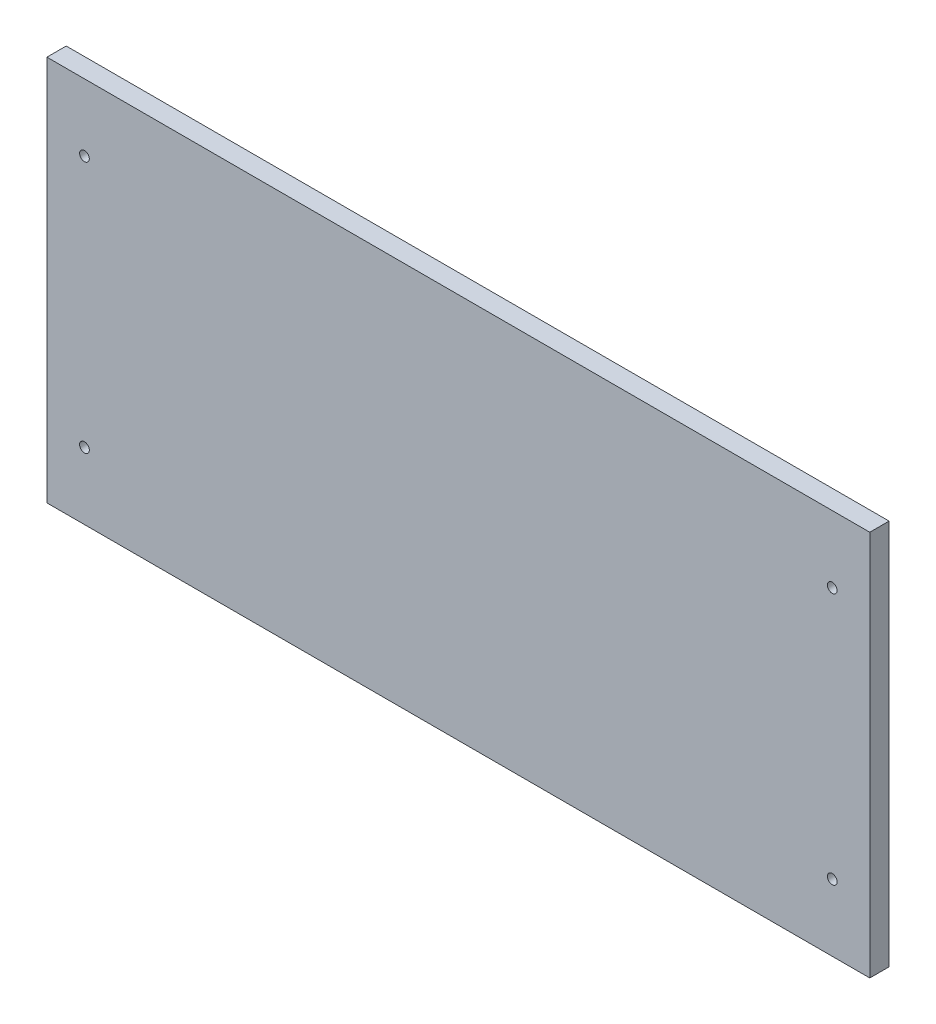
SolidWorks part; units mm, degrees
material "Acrylic (Medium-high impact)"
ref_plane "Front Plane" through (0, 0, 0) normal (0, 0, 1) x (1, 0, 0)
ref_plane "Top Plane" through (0, 0, 0) normal (0, 1, 0) x (1, 0, 0)
ref_plane "Right Plane" through (0, 0, 0) normal (1, 0, 0) x (0, 0, -1)
sketch "Sketch1" plane through (0, 0, 0) normal (0, 0, 1) x (1, 0, 0)
  line L0 (135.35, 127) -> (135.35, 0) construction
  line L1 (0, 0) -> (270.7, 0)
  line L2 (0, 0) -> (0, 127)
  line L3 (0, 127) -> (270.7, 127)
  line L4 (270.7, 0) -> (270.7, 127)
  line L5 (0, 63.5) -> (270.7, 63.5) construction
  circle A3 centre (12.35, 105) radius 1.6
  circle A7 centre (258.35, 105) radius 1.6
  circle A8 centre (258.35, 22) radius 1.6
  circle A9 centre (12.35, 22) radius 1.6
  dimension "D11" = 3.2
  dimension "D1" = 127
  dimension "D2" = 270.7
  dimension "D12" = 12.35
  dimension "D13" = 22
extrude "Wall" add sketch "Sketch1" along normal blind 6.35
sketch "Sketch10" [suppressed] plane through (0, 0, 6.35) normal (0, 0, 1) x (1, 0, 0)
  line L0 (0, 0) -> (270.7, 38.0444)
  line L1 (270.7, 0) -> (270.7, 127) construction
  line L2 (270.7, 38.0444) -> (270.7, 0)
  line L3 (270.7, 0) -> (0, 0)
  dimension "D1" = 8
extrude "Cut-Extrude4" [suppressed] cut sketch "Sketch10" against normal through all
equation "\"Length\"= 283mm"
equation "\"Width\"= 225mm"
equation "\"WallThickness\"= 0.25in"
equation "\"UpperWaterJacketThickness\"= 28mm"
equation "\"SpacerHeight\"= 80.2mm"
equation "\"SpacerCornerWidth\"= 10mm"
equation "\"SpacerCornerHeight\"= 60.16mm"
equation "\"SpacerPegDiameter\"= 10mm"
equation "\"SpacerPegHeight\"= 10mm"
equation "\"TubingShort\"= 110mm"
equation "\"TubingLong\"= 175mm"
equation "\"PlateLength\"= 252mm"
equation "\"PlateWidth\"= 190mm"
equation "\"PlateHoleDiameter\"= 5.9mm"
equation "\"PlateHoleBottom\"= 2mm"
equation "\"PlateHoleSide\"= 1.55mm"
equation "\"PlateHoleSpacing\"= 3.1mm"
equation "\"PlateThickness\"= 1.55mm"
equation "\"ReservoirBottom\"= 12.5mm"
equation "\"ReservoirSupportWidth\"= 12mm"
equation "\"ReservoirSupportHeight\"= 15.1mm"
equation "\"ReservoirSupportPlacementHeight\"= 50mm"
equation "\"ReservoirHoleDiameter\"= 12.7mm"
equation "\"ReservoirHoleRight\"= 25mm"
equation "\"ReservoirHoleTop\"= \"ReservoirSupportPlacementHeight\""
equation "\"ReservoirHeight\"= 90mm"
equation "\"ReservoirPortBottom\"= 4mm"
equation "\"ReservoirPortTop\"= 10mm"
equation "\"ReservoirPortWidth\"= 101mm"
equation "\"CustomSpacerHeight\"= 5in"
equation "\"CustomSpacerRodHoleHeight\"= .75in"
equation "\"CustomSpacerRodHoleDiameter\"= .3125in"
equation "\"ScrewBlockSide\"= 12mm"
equation "\"ScrewBlockUpperHeight\"= 16mm"
equation "\"ScrewBlockLowerHeight\"= 16mm"
equation "\"InternalLength\"= 258mm"
equation "\"InternalWidth\"= 200mm"
equation "\"CustomSpacerPegHeight\"= 1in"
equation "\"CustomSpacerScrewBore\"=3.2mm"
equation "\"CustomSpacerScrewDepth\"=10mm"
equation "\"D1@Sketch1\" = \"CustomSpacerHeight\""
equation "\"D2@Sketch1\"=\"WallLength\""
equation "\"D11@Sketch1\"=\"CustomSpacerScrewBore\""
equation "\"D13@Sketch1\"=\"ScrewBlockUpperHeight\"+\"ScrewBlockSide\"/2"
equation "\"D1@Wall\" = \"WallThickness\""
equation "\"WallLength\"= \"InternalLength\" + ( 2 * \"WallThickness\" )"
